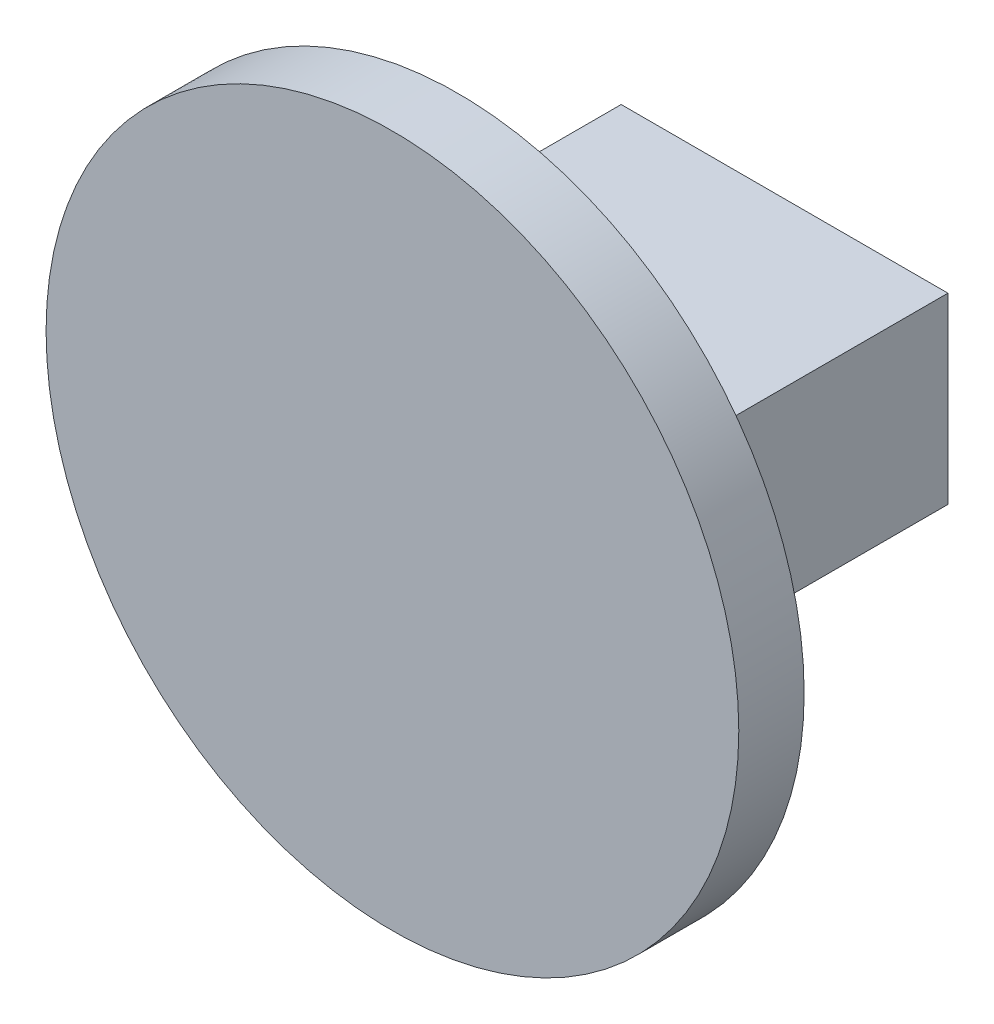
SolidWorks part; units mm, degrees
ref_plane "Front Plane" through (0, 0, 0) normal (0, 0, 1) x (1, 0, 0)
ref_plane "Top Plane" through (0, 0, 0) normal (0, 1, 0) x (1, 0, 0)
ref_plane "Right Plane" through (0, 0, 0) normal (1, 0, 0) x (0, 0, -1)
sketch "Sketch1" plane through (0, 0, 0) normal (0, 0, 1) x (1, 0, 0)
  circle A0 centre (0, 0) radius 1346.2
extrude "Boss-Extrude3" add sketch "Sketch1" along normal blind 254 contours A0
sketch "Sketch2" plane through (0, 0, 0) normal (0, 0, 1) x (1, 0, 0)
  line L0 (1264.9738, -460.5386) -> (-1264.9738, -460.5386)
  line L1 (-635, -355.6) -> (635, -355.6)
  line L2 (-635, -355.6) -> (-635, 355.6)
  line L3 (-635, 355.6) -> (635, 355.6)
  line L4 (635, -355.6) -> (635, 355.6)
  line L5 (-635, -355.6) -> (635, 355.6) construction
  line L6 (-635, 355.6) -> (635, -355.6) construction
  circle A0 centre (965.2, 0) radius 254
  circle A1 centre (-965.2, 0) radius 254
  circle A2 centre (0, 965.2) radius 254
  circle A3 centre (0, 0) radius 1346.2 construction
  point P6 (0, 0)
  point P16 (2433.1079, 781.3634)
  point P17 (0, 0)
  point P18 (-1264.9738, -460.5386)
  point P19 (-1264.9738, -460.5386)
extrude "Boss-Extrude6" add sketch "Sketch2" against normal blind 1270 contours L1 L4 L3 L2
